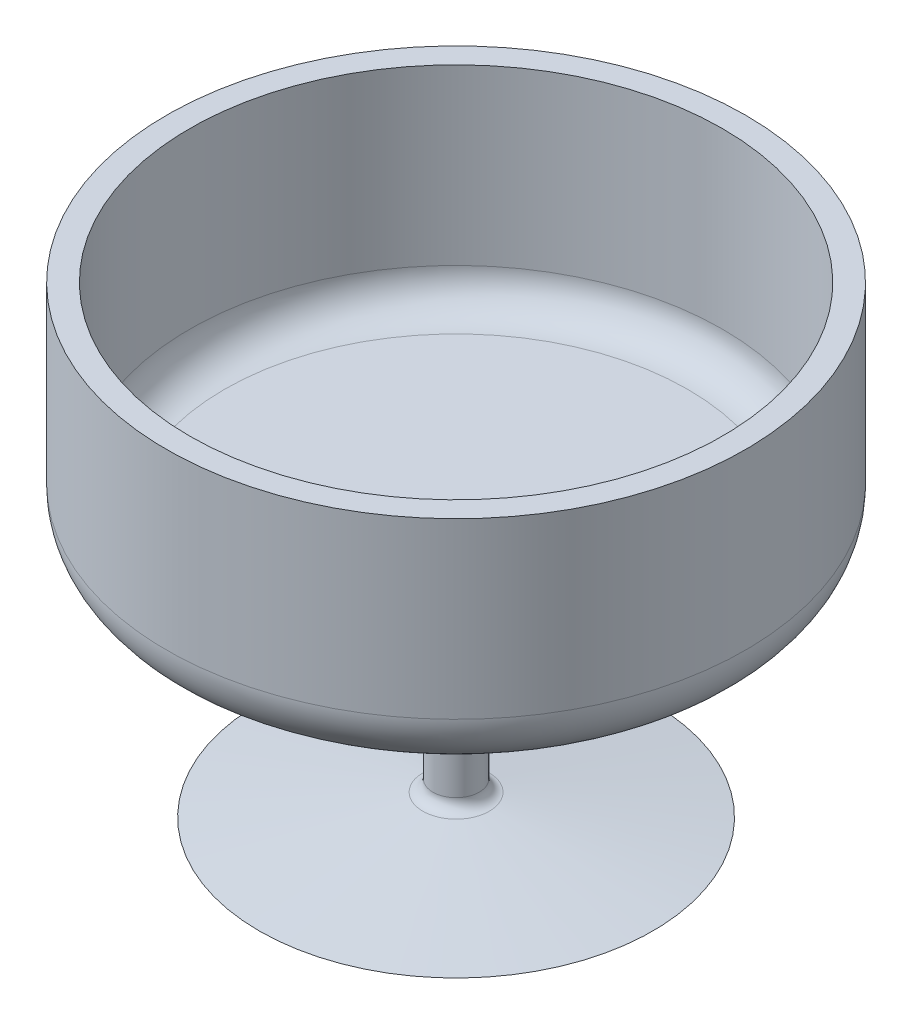
SolidWorks part; units mm, degrees
ref_plane "前基準面" through (0, 0, 0) normal (0, 0, 1) x (1, 0, 0)
ref_plane "上基準面" through (0, 0, 0) normal (0, 1, 0) x (1, 0, 0)
ref_plane "右基準面" through (0, 0, 0) normal (1, 0, 0) x (0, 0, -1)
sketch "草圖1" plane through (0, 0, 0) normal (0, 0, 1) x (1, 0, 0)
  line L0 (0, 0) -> (0, 40)
  line L1 (0, 40) -> (25, 40)
  line L2 (25, 40) -> (25, 20)
  line L3 (25, 20) -> (2, 20)
  line L4 (2, 20) -> (2, 2)
  line L5 (2, 2) -> (17, 0)
  line L6 (17, 0) -> (0, 0)
  point P4 (8.5, 0)
  dimension "D1" = 40
  dimension "D2" = 20
  dimension "D3" = 2
  dimension "D4" = 2
  dimension "D5" = 17
  dimension "D6" = 25
revolve "旋轉1" add sketch "草圖1" angle 360 about L0
fillet "圓角1" radius 5 1 edges at (0, 20, -25)
fillet "圓角2" radius 1 1 edges at (0, 2, -2)
sketch "草圖2" plane through (0, 0, 0) normal (0, 0, 1) x (1, 0, 0)
  line L4 (23, 40) -> (0, 40)
  line L5 (25, 40) -> (-25, 40) construction
  line L6 (-20, 22) -> (20, 22)
  line L7 (23, 25) -> (23, 40)
  line L8 (0, 22) -> (20, 22)
  line L9 (23, 25) -> (23, 40)
  line L10 (0, 40) -> (0, 22)
  arc A3 (20, 22) -> (23, 25) centre (20, 25) ccw
  arc A4 (20, 22) -> (23, 25) centre (20, 25) ccw
  dimension "D1" = 2
revolve "除料-旋轉1" cut sketch "草圖2" angle 360 about L10
